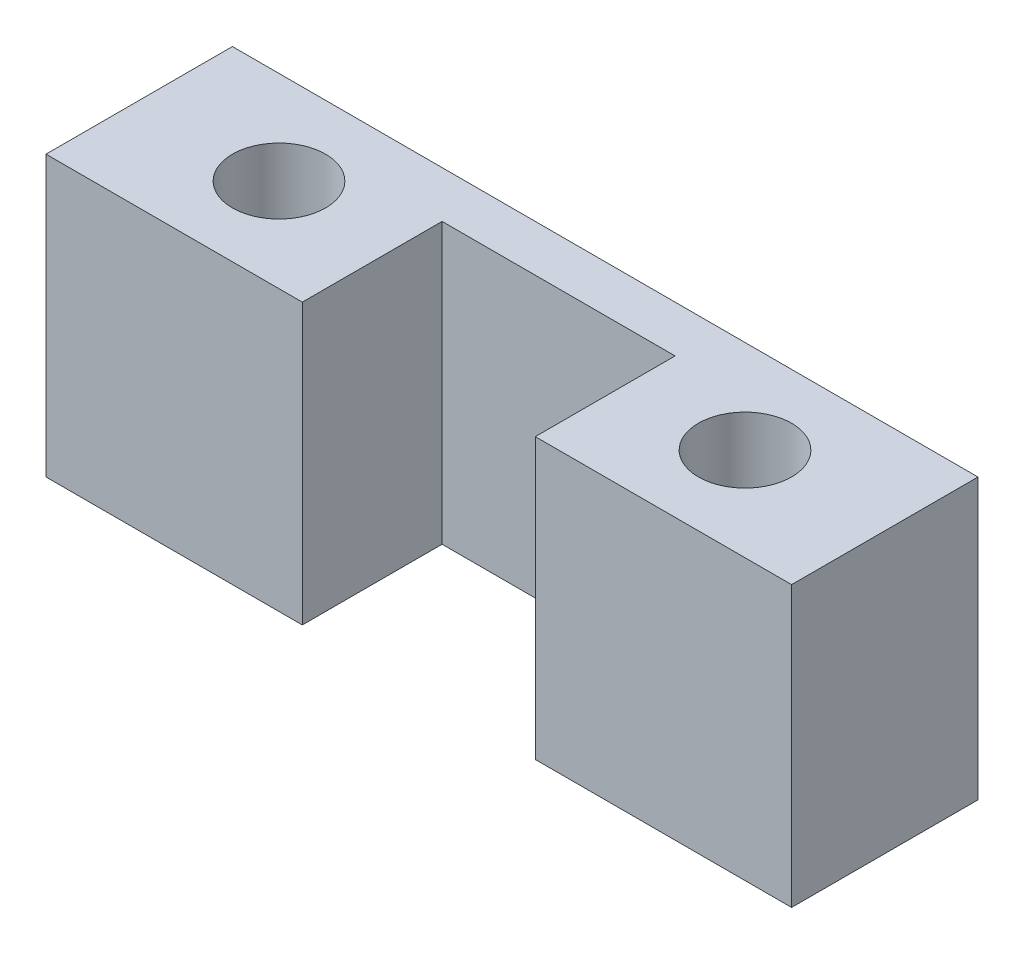
SolidWorks part; units mm, degrees
material "6061 Alloy"
ref_plane "Front Plane" through (0, 0, 0) normal (0, 0, 1) x (1, 0, 0)
ref_plane "Top Plane" through (0, 0, 0) normal (0, 1, 0) x (1, 0, 0)
ref_plane "Right Plane" through (0, 0, 0) normal (1, 0, 0) x (0, 0, -1)
sketch "Sketch1" plane through (0, 0, 0) normal (0, 1, 0) x (1, 0, 0)
  line L1 (-25.4, -6.35) -> (25.4, -6.35)
  line L2 (-25.4, -6.35) -> (-25.4, 6.35)
  line L3 (-25.4, 6.35) -> (25.4, 6.35)
  line L4 (25.4, -6.35) -> (25.4, 6.35)
  line L5 (-25.4, -6.35) -> (25.4, 6.35) construction
  line L6 (-25.4, 6.35) -> (25.4, -6.35) construction
  point P0 (0, 0)
  dimension "D1" = 50.8
  dimension "D2" = 12.7
extrude "Boss-Extrude1" add sketch "Sketch1" along normal blind 19.05
sketch "Sketch2" plane through (0, 19.05, 0) normal (0, 1, 0) x (1, 0, 0)
  circle A0 centre (-15.875, 0) radius 3.175
  circle A1 centre (15.875, 0) radius 3.175
  dimension "D1" = 6.35
  dimension "D2" = 6.35
  dimension "D3" = 31.75
  dimension "D4" = 15.875
extrude "Cut-Extrude1" cut sketch "Sketch2" against normal blind 15.875
sketch "Sketch3" plane through (0, 19.05, 0) normal (0, 1, 0) x (1, 0, 0)
  line L0 (-25.4, -6.35) -> (25.4, -6.35) construction
  line L1 (-7.9375, -6.35) -> (7.9375, -6.35)
  line L2 (-7.9375, -6.35) -> (-7.9375, 3.175)
  line L3 (-7.9375, 3.175) -> (7.9375, 3.175)
  line L4 (7.9375, -6.35) -> (7.9375, 3.175)
  dimension "D1" = 15.875
  dimension "D2" = 7.9375
  dimension "D3" = 9.525
extrude "Cut-Extrude2" cut sketch "Sketch3" against normal through all
